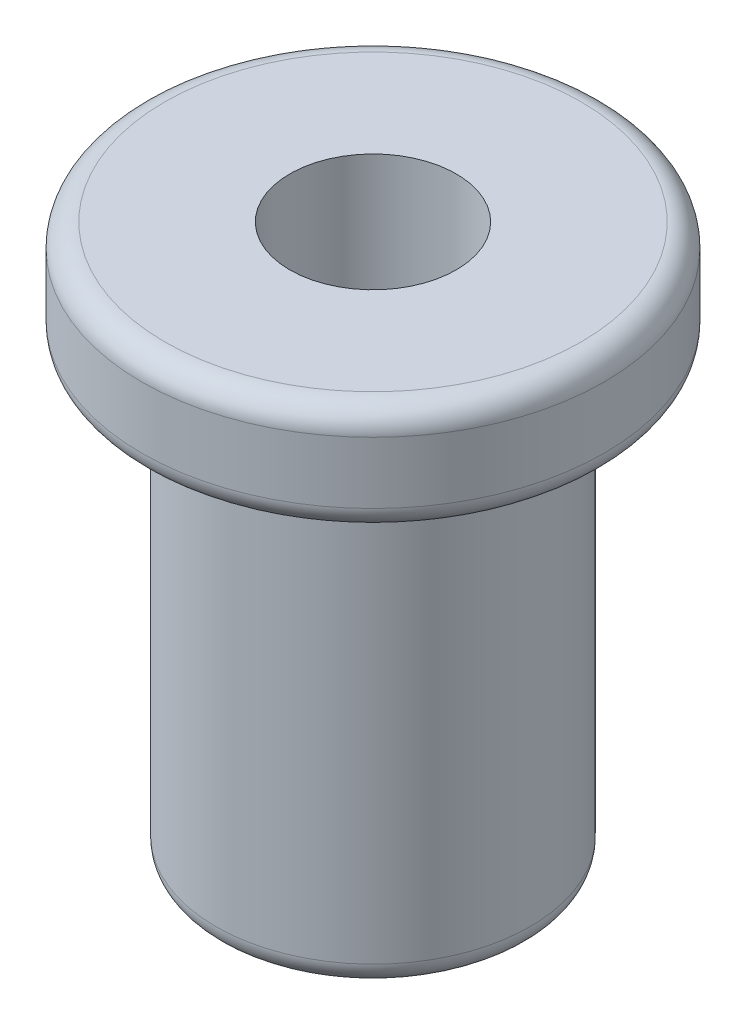
SolidWorks part; units mm, degrees
material "Rubber"
ref_plane "Front Plane" through (0, 0, 0) normal (0, 0, 1) x (1, 0, 0)
ref_plane "Top Plane" through (0, 0, 0) normal (0, 1, 0) x (1, 0, 0)
ref_plane "Right Plane" through (0, 0, 0) normal (1, 0, 0) x (0, 0, -1)
sketch "Sketch1" plane through (0, 0, 0) normal (1, 0, 0) x (0, 0, -1)
  line L0 (2.7, 0) -> (2.7, -15)
  line L1 (2.7, -15) -> (2, -15)
  line L2 (2, -15) -> (2, -18)
  line L3 (2, -18) -> (5.1, -18)
  line L4 (5.1, -18) -> (5.1, -3.5)
  line L5 (5.1, -3.5) -> (7.5, -3.5)
  line L6 (7.5, -3.5) -> (7.5, 0)
  line L7 (7.5, 0) -> (2.7, 0)
  line L8 (0, 0) -> (0, -9.3814) construction
  dimension "D1" = 5.4
  dimension "D2" = 15
  dimension "D3" = 15
  dimension "D4" = 3.5
  dimension "D5" = 10.2
  dimension "D6" = 14.5
  dimension "D7" = 4
revolve "Revolve1" add sketch "Sketch1" angle 360 about L8
fillet "Fillet1" radius 0.75 3 edges at (0, -18, 5.1) (0, -3.5, 7.5) (0, 0, 7.5)
